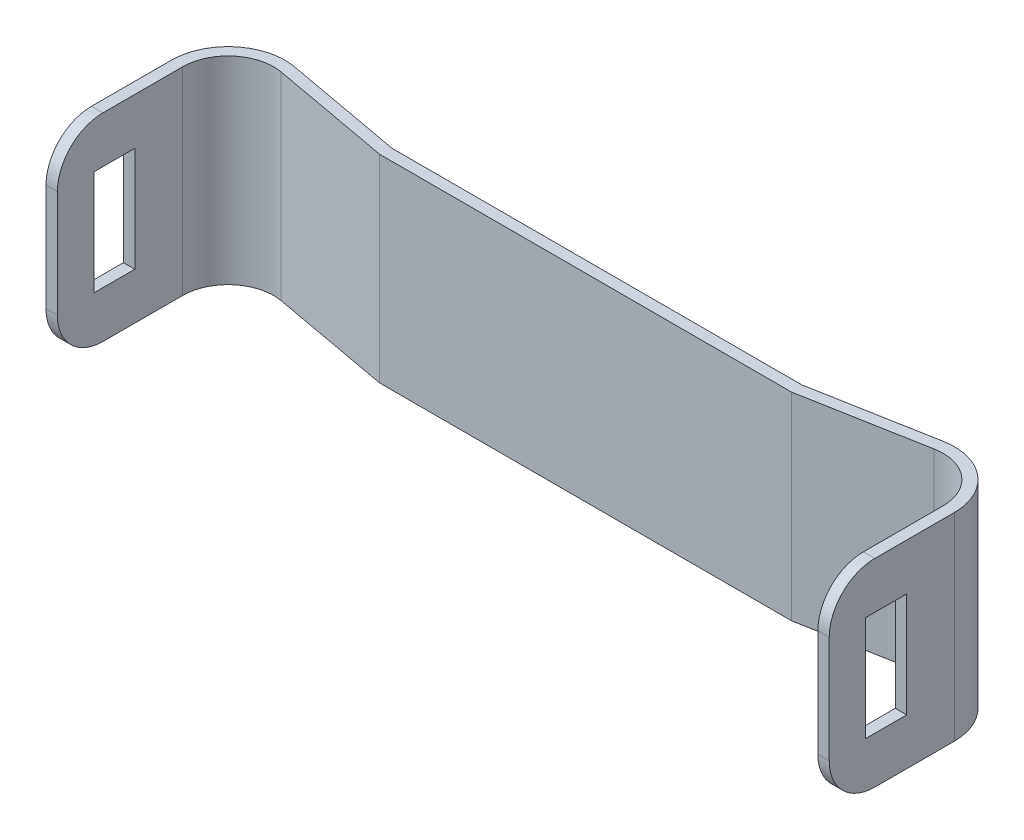
SolidWorks part; units mm, degrees
ref_plane "Plane1" through (0, 0, 0) normal (0, 0, 1) x (1, 0, 0)
ref_plane "Plane2" through (0, 0, 0) normal (0, 1, 0) x (1, 0, 0)
ref_plane "Plane3" through (0, 0, 0) normal (1, 0, 0) x (0, 0, -1)
sketch "Sketch1" plane through (0, 0, 0) normal (0, 1, 0) x (1, 0, 0)
  line L0 (-9, 0) -> (9, 0)
  line L1 (9, 0) -> (14.2507, 0.9593)
  line L2 (17.2, -1.5) -> (17.2, -7)
  line L3 (0, 9) -> (0, -9) construction
  line L4 (-17.2, -1.5) -> (-17.2, -7)
  line L5 (-9, 0) -> (-14.2507, 0.9593)
  arc A0 (14.2507, 0.9593) -> (17.2, -1.5) centre (14.7, -1.5) cw
  arc A1 (-14.2507, 0.9593) -> (-17.2, -1.5) centre (-14.7, -1.5) ccw
  point P14 (0, 0)
  dimension "D3" = 2.5
  dimension "D4" = 8
  dimension "D1" = 17.2
  dimension "D2" = 9
  dimension "D5" = 1
extrude "Base-Extrude-Thin" add sketch "Sketch1" along normal mid plane 8.7 thin
sketch "Sketch2" plane through (17.2, 0, 0) normal (1, 0, 0) x (0, 0, -1)
  line L0 (-7, 4.35) -> (-7, -4.35) construction
  line L1 (-5.4, 2.3) -> (-3.6, 2.3)
  line L2 (-5.4, 2.3) -> (-5.4, -2.3)
  line L3 (-5.4, -2.3) -> (-3.6, -2.3)
  line L4 (-3.6, 2.3) -> (-3.6, -2.3)
  line L6 (-7, 4.35) -> (-1.5, 4.35) construction
  line L7 (-7, 2.35) -> (-7, -2.35)
  line L8 (-5, 4.35) -> (-5, 8)
  line L9 (-5, 8) -> (-10, 8)
  line L10 (-10, 8) -> (-10, -8)
  line L11 (-11, 0) -> (-8, 0) construction
  line L12 (-5, -8) -> (-10, -8)
  line L13 (-5, -4.35) -> (-5, -8)
  arc A0 (-7, 2.35) -> (-5, 4.35) centre (-5, 2.35) cw
  arc A1 (-7, -2.35) -> (-5, -4.35) centre (-5, -2.35) ccw
  point P4 (-3.6, 0)
  point P23 (-10, 0)
  point P24 (-7, 0)
  dimension "D4" = 2
  dimension "D1" = 4.6
  dimension "D2" = 1.8
  dimension "D3" = 1.6
  dimension "D5" = 3
  dimension "D6" = 16
extrude "Cut-Extrude1" cut sketch "Sketch2" against normal through all
